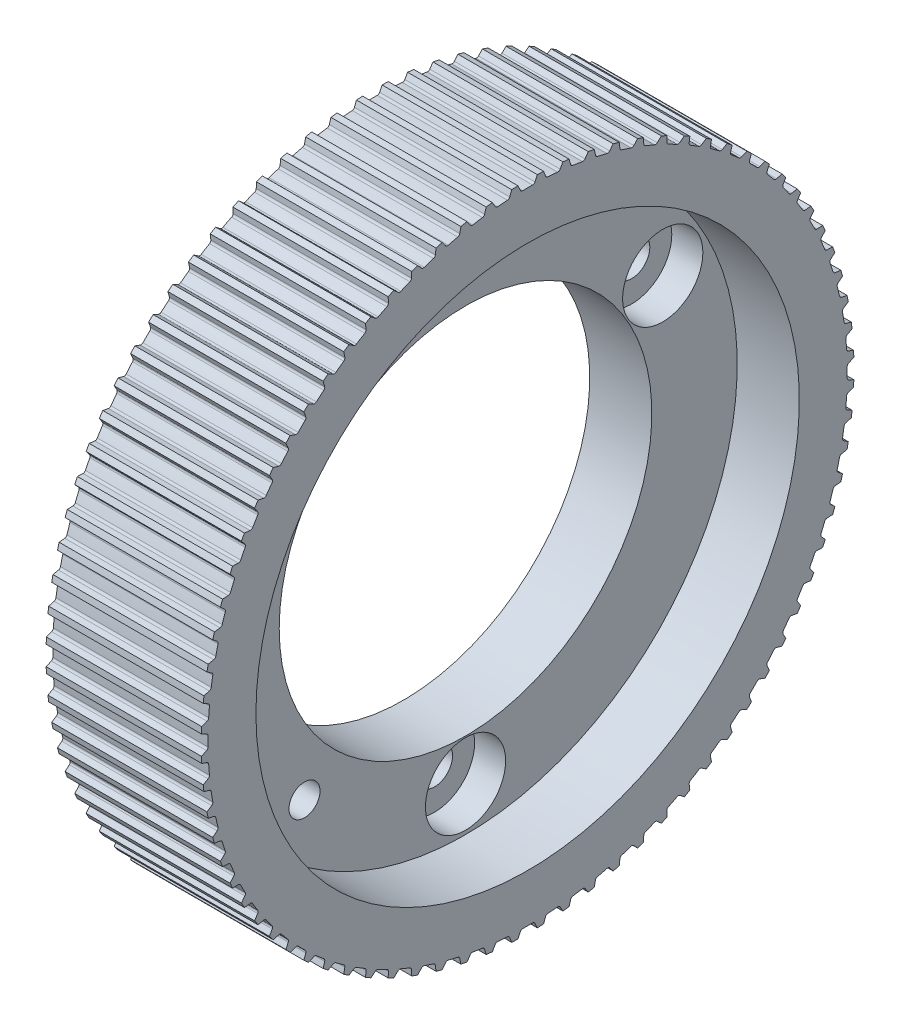
SolidWorks part; units mm, degrees
material "Alliage 1060"
ref_plane "Plan de face" through (0, 0, 0) normal (0, 0, 1) x (1, 0, 0)
ref_plane "Plan de dessus" through (0, 0, 0) normal (0, 1, 0) x (1, 0, 0)
ref_plane "Plan de droite" through (0, 0, 0) normal (1, 0, 0) x (0, 0, -1)
sketch "Esquisse1" plane through (0, 0, 0) normal (0, 0, 1) x (1, 0, 0)
  line L0 (-35.3225, 0) -> (46.8564, 0) construction
  line L1 (0, 36) -> (0, 49)
  line L2 (0, 49) -> (-6, 49)
  line L3 (-6, 49) -> (-6, 63.05)
  line L4 (-6, 63.05) -> (24, 63.05)
  line L5 (24, 63.05) -> (24, 52.5)
  line L6 (24, 52.5) -> (12, 52.5)
  line L7 (12, 52.5) -> (12, 36)
  line L8 (12, 36) -> (0, 36)
  dimension "D1" = 72
  dimension "D2" = 126.1
  dimension "D3" = 98
  dimension "D4" = 105
  dimension "D5" = 30
  dimension "D6" = 6
  dimension "D7" = 12
revolve "Révolution1" add sketch "Esquisse1" angle 360 about L0
sketch "Esquisse2" plane through (12, 0, 0) normal (1, 0, 0) x (0, 0, -1)
  line L0 (-68.9482, 0) -> (69.4157, 0) construction
  line L1 (0, 0) -> (-31.1127, -31.1127) construction
  line L3 (0, 3.6227) -> (0, 57.8464) construction
  circle A0 centre (0, 44) radius 3
  circle A1 centre (-31.1127, -31.1127) radius 3
  circle A2 centre (0, -44) radius 3.5
  circle A3 centre (-38.1051, 22) radius 3.5
  circle A4 centre (38.1051, 22) radius 3.5
  dimension "D4" = 6
  dimension "D6" = 7
  dimension "D1" = 135
  dimension "D2" = 44
  dimension "D3" = 44
  dimension "D5" = 44
extrude "Enlèv. mat.-Extru.1" cut sketch "Esquisse2" against normal up to next
sketch "Esquisse3" plane through (12, 0, 0) normal (1, 0, 0) x (0, 0, -1)
  circle A0 centre (0, -44) radius 7.75
  dimension "D1" = 15.5
extrude "Enlèv. mat.-Extru.3" cut sketch "Esquisse3" against normal blind 6
pattern_circular "Répétition circulaire1" count 3 every 120 about axis through (0, 0, 0) along (1, 0, 0) of "Enlèv. mat.-Extru.3"
sketch "Esquisse4" plane through (24, 0, 0) normal (1, 0, 0) x (0, 0, -1)
  line L0 (0, 44) -> (0, 75.6014) construction
  line L1 (-2.155, 63.6335) -> (-1.4079, 62.0314)
  line L2 (2.155, 63.6335) -> (1.4079, 62.0314)
  arc A0 (-0.9471, 61.7427) -> (0.9471, 61.7427) centre (0, 0) cw
  arc A1 (-2.155, 63.6335) -> (2.155, 63.6335) centre (0, 0) cw
  arc A2 (-0.9471, 61.7427) -> (-1.4079, 62.0314) centre (-0.9548, 62.2427) cw
  arc A3 (1.4079, 62.0314) -> (0.9471, 61.7427) centre (0.9548, 62.2427) cw
  point P11 (-1.2706, 61.7369)
  point P14 (1.2706, 61.7369)
  dimension "D1" = 63.67
  dimension "D2" = 61.75
  dimension "D6" = 0.5
  dimension "D3" = 4.31
  dimension "D5" = 50
extrude "Enlèv. mat.-Extru.4" cut sketch "Esquisse4" against normal up to next
pattern_circular "Répétition circulaire2" count 80 every 4.5 about axis through (0, 0, 0) along (1, 0, 0) of "Enlèv. mat.-Extru.4"
